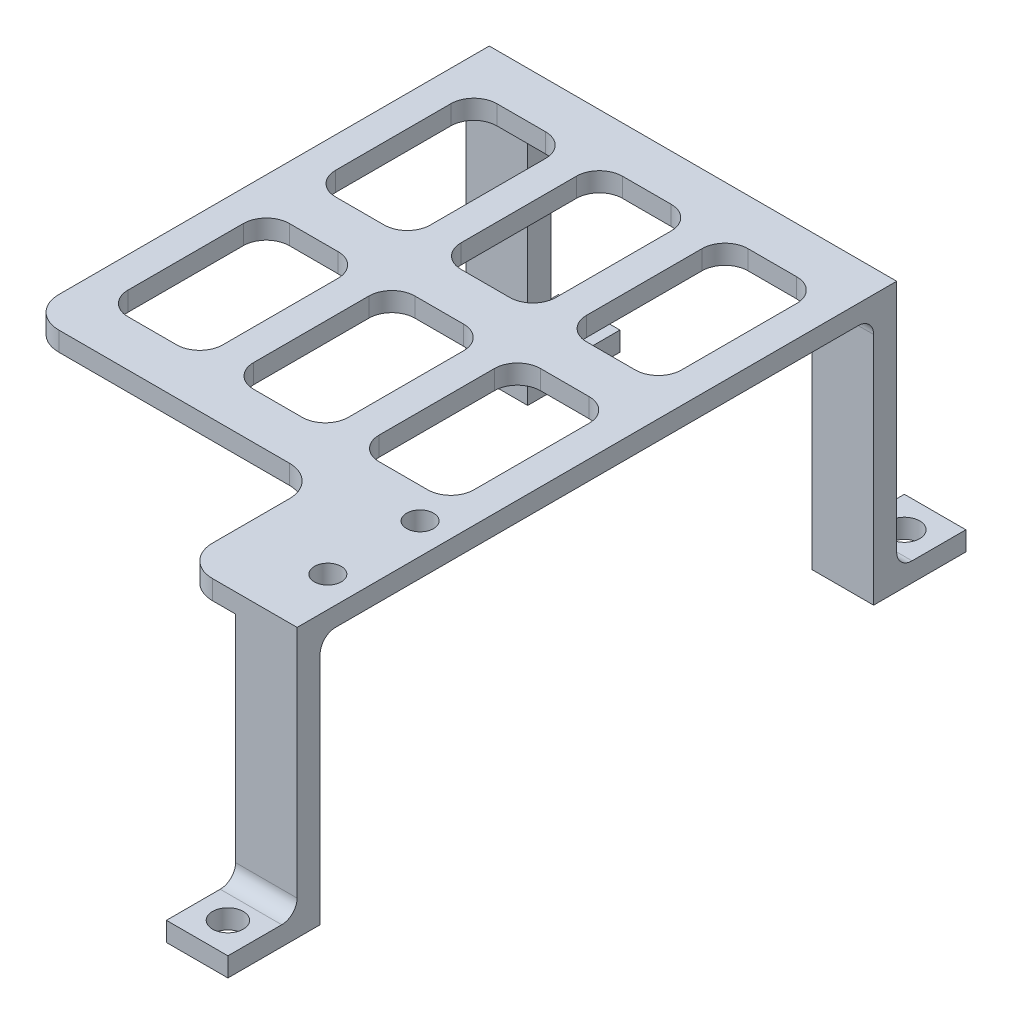
SolidWorks part; units mm, degrees
ref_plane "Front Plane" through (0, 0, 0) normal (0, 0, 1) x (1, 0, 0)
ref_plane "Top Plane" through (0, 0, 0) normal (0, 1, 0) x (1, 0, 0)
ref_plane "Right Plane" through (0, 0, 0) normal (1, 0, 0) x (0, 0, -1)
sketch "Sketch1" plane through (0, 0, 0) normal (0, 1, 0) x (1, 0, 0)
  line L1 (-45, 84) -> (-37, 84)
  line L2 (-45, 84) -> (-45, 72)
  line L3 (-45, 72) -> (-37, 72)
  line L4 (-37, 84) -> (-37, 72)
  line L5 (0, 0) -> (8, 0)
  line L6 (0, 0) -> (0, -12)
  line L7 (0, -12) -> (8, -12)
  line L8 (8, 0) -> (8, -12)
  line L9 (0, 72) -> (8, 72)
  line L10 (0, 72) -> (0, 84)
  line L11 (0, 84) -> (8, 84)
  line L12 (8, 72) -> (8, 84)
  circle A0 centre (-41, 80) radius 2
  circle A1 centre (4, 80) radius 2
  circle A2 centre (4, -8) radius 2
  dimension "D1" = 4
  dimension "D2" = 4
  dimension "D3" = 4
  dimension "D4" = 4
  dimension "D5" = 4
  dimension "D6" = 8
  dimension "D7" = 45
  dimension "D8" = 4
  dimension "D9" = 8
  dimension "D10" = 4
  dimension "D11" = 88
extrude "Boss-Extrude1" add sketch "Sketch1" along normal blind 2.5
sketch "Sketch2" plane through (0, 2.5, 0) normal (0, 1, 0) x (1, 0, 0)
  line L0 (-37, 72) -> (-37, 84) construction
  line L1 (-45, 72) -> (-37, 72)
  line L2 (-45, 72) -> (-45, 75)
  line L3 (-45, 75) -> (-37, 75)
  line L4 (-37, 72) -> (-37, 75)
  line L5 (8, 72) -> (8, 84) construction
  line L6 (0, 72) -> (8, 72)
  line L7 (0, 72) -> (0, 75)
  line L8 (0, 75) -> (8, 75)
  line L9 (8, 72) -> (8, 75)
  line L10 (8, -12) -> (8, 0) construction
  line L11 (0, 0) -> (8, 0)
  line L12 (0, 0) -> (0, -3)
  line L13 (0, -3) -> (8, -3)
  line L14 (8, 0) -> (8, -3)
  dimension "D1" = 3
  dimension "D2" = 3
  dimension "D3" = 3
extrude "Boss-Extrude2" add sketch "Sketch2" along normal blind 30
sketch "Sketch3" plane through (0, 32.5, 0) normal (0, 1, 0) x (1, 0, 0)
  line L0 (8, -3) -> (8, 0) construction
  line L1 (-45, 75) -> (8, 75)
  line L2 (-45, 75) -> (-45, 15)
  line L3 (-7, -3) -> (8, -3)
  line L4 (8, 75) -> (8, -3)
  line L8 (-45, 15) -> (-7, 15)
  line L9 (-7, -3) -> (-7, 15)
  line L10 (-41, 69) -> (-45, 69) construction
  line L11 (-41, 69) -> (-28.6667, 69)
  line L12 (-41, 69) -> (-41, 48)
  line L13 (-41, 48) -> (-28.6667, 48)
  line L14 (-28.6667, 69) -> (-28.6667, 48)
  line L15 (-24.6667, 69) -> (-12.3333, 69)
  line L16 (-24.6667, 69) -> (-24.6667, 48)
  line L17 (-24.6667, 48) -> (-12.3333, 48)
  line L18 (-12.3333, 69) -> (-12.3333, 48)
  line L19 (-8.3333, 69) -> (4, 69)
  line L20 (-8.3333, 69) -> (-8.3333, 48)
  line L21 (-8.3333, 48) -> (4, 48)
  line L22 (4, 69) -> (4, 48)
  line L23 (-41, 42) -> (-28.6667, 42)
  line L24 (-41, 42) -> (-41, 21)
  line L25 (-41, 21) -> (-28.6667, 21)
  line L26 (-28.6667, 42) -> (-28.6667, 21)
  line L27 (-24.6667, 42) -> (-12.3333, 42)
  line L28 (-24.6667, 42) -> (-24.6667, 21)
  line L29 (-24.6667, 21) -> (-12.3333, 21)
  line L30 (-12.3333, 42) -> (-12.3333, 21)
  line L31 (-8.3333, 42) -> (4, 42)
  line L32 (-8.3333, 42) -> (-8.3333, 21)
  line L33 (-8.3333, 21) -> (4, 21)
  line L34 (4, 42) -> (4, 21)
  line L35 (-28.6667, 69) -> (-24.6667, 69) construction
  line L36 (-12.3333, 69) -> (-8.3333, 69) construction
  line L37 (4, 69) -> (8, 69) construction
  line L38 (-41, 69) -> (-41, 75) construction
  line L39 (-41, 48) -> (-41, 42) construction
  line L40 (-41, 21) -> (-41, 15) construction
  circle A0 centre (4, 5) radius 1.75
  circle A1 centre (4, 17) radius 1.75
  dimension "D1" = 3.5
  dimension "D2" = 3.5
  dimension "D3" = 12
  dimension "D4" = 15
  dimension "D5" = 18
  dimension "D6" = 4
  dimension "D7" = 8
  dimension "D8" = 4
  dimension "D9" = 6
extrude "Boss-Extrude3" add sketch "Sketch3" along normal blind 2.5
fillet "Fillet1" radius 3 24 edges at (-41, 33.75, -48) (-24.6667, 33.75, -48) (-8.3333, 33.75, -48) (-8.3333, 33.75, -21) (-24.6667, 33.75, -21) (-41, 33.75, -21) (-28.6667, 33.75, -48) (-28.6667, 33.75, -21) (-12.3333, 33.75, -21) (-12.3333, 33.75, -48) (4, 33.75, -21) (4, 33.75, -48) (4, 33.75, -69) (-28.6667, 33.75, -42) (-12.3333, 33.75, -42) (4, 33.75, -42) (-12.3333, 33.75, -69) (-28.6667, 33.75, -69) (-8.3333, 33.75, -69) (-24.6667, 33.75, -42) (-8.3333, 33.75, -42) (-41, 33.75, -42) (-24.6667, 33.75, -69) (-41, 33.75, -69)
fillet "Fillet2" radius 4 3 edges at (-7, 33.75, 3) (-7, 33.75, -15) (-45, 33.75, -15)
fillet "Fillet3" radius 2 3 edges at (4, 2.5, 3) (-41, 2.5, -75) (4, 2.5, -75)
fillet "Fillet4" radius 2 3 edges at (4, 32.5, 0) (4, 32.5, -72) (-41, 32.5, -72)
